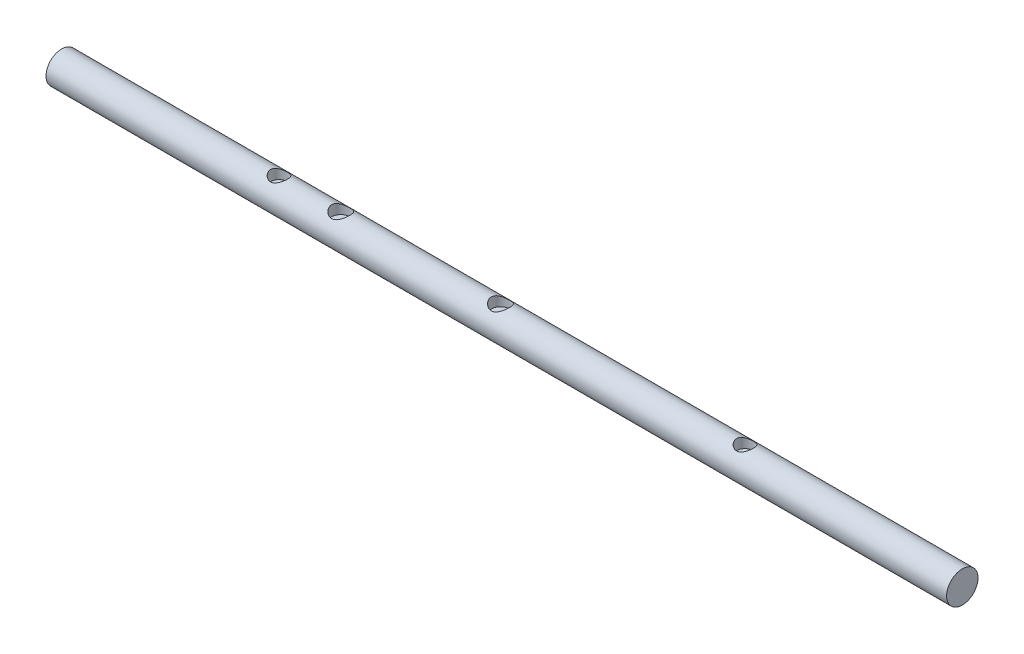
SolidWorks part; units mm, degrees
ref_plane "Ön Düzlem" through (0, 0, 0) normal (0, 0, 1) x (1, 0, 0)
ref_plane "Üst Düzlem" through (0, 0, 0) normal (0, 1, 0) x (1, 0, 0)
ref_plane "Sağ Düzlem" through (0, 0, 0) normal (1, 0, 0) x (0, 0, -1)
sketch "Sketch1" plane through (0, 0, 0) normal (0, 0, 1) x (1, 0, 0)
  line L1 (-158.8073, 1.9024) -> (13.1927, 1.9024)
  line L2 (-158.8073, 1.9024) -> (-158.8073, -1.0976)
  line L3 (-158.8073, -1.0976) -> (13.1927, -1.0976)
  line L4 (13.1927, 1.9024) -> (13.1927, -1.0976)
  dimension "D1" = 3
  dimension "D2" = 172
revolve "Revolve1" add sketch "Sketch1" angle 360 about L1
sketch "Sketch2" plane through (-158.8073, 0, 0) normal (-1, 0, 0) x (0, 0, 1)
  line L0 (0, 1.9024) -> (0, 4.9024)
  circle A0 centre (0, 1.9024) radius 3 construction
ref_plane "Plane1" through (-158.8073, 4.9024, 0) normal (0, 1, 0) x (1, 0, 0)
sketch "Sketch3" plane through (-158.8073, 4.9024, 0) normal (0, 1, 0) x (1, 0, 0)
  line L0 (0, 0) -> (31, 0)
  line L1 (0, 3) -> (0, -3) construction
  line L2 (172, 0) -> (141, 0)
  line L3 (172, -3) -> (172, 3) construction
  line L4 (31, 0) -> (39, 0)
  line L5 (141, 0) -> (133, 0)
  line L6 (0, 0) -> (83.8, 0)
  line L7 (39, 0) -> (41.5, 0)
  line L8 (39, 0) -> (53.3, 0)
  line L9 (133, 0) -> (130.5, 0)
  circle A0 centre (83.8, 0) radius 1.75
  circle A1 centre (41.5, 0) radius 1.6
  circle A2 centre (53.3, 0) radius 1.75
  circle A3 centre (130.5, 0) radius 1.6
  dimension "D6" = 3.5
  dimension "D8" = 3.2
  dimension "D10" = 3.5
  dimension "D12" = 3.2
  dimension "D1" = 31
  dimension "D2" = 31
  dimension "D3" = 8
  dimension "D4" = 8
  dimension "D5" = 83.8
  dimension "D7" = 2.5
  dimension "D9" = 14.3
  dimension "D11" = 2.5
extrude "Cut-Extrude1" cut sketch "Sketch3" against normal blind 2
